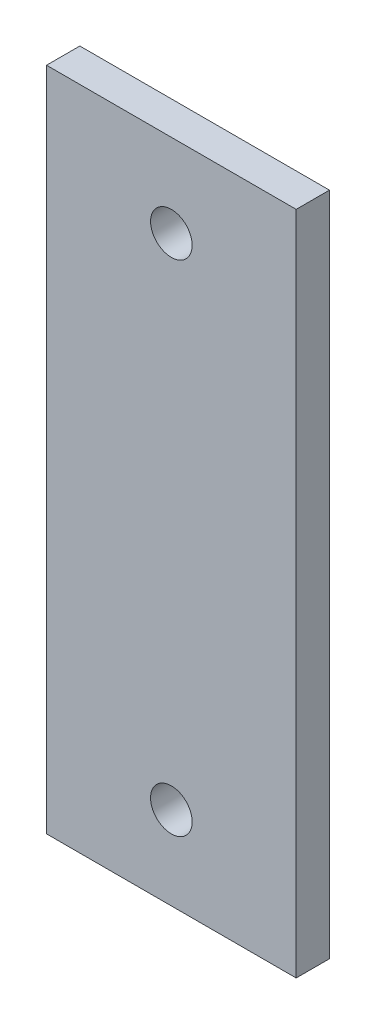
SolidWorks part; units mm, degrees
material "Balsa"
ref_plane "Plan de face" through (0, 0, 0) normal (0, 0, 1) x (1, 0, 0)
ref_plane "Plan de dessus" through (0, 0, 0) normal (0, 1, 0) x (1, 0, 0)
ref_plane "Plan de droite" through (0, 0, 0) normal (1, 0, 0) x (0, 0, -1)
sketch "Esquisse1" plane through (0, 0, 0) normal (0, 0, 1) x (1, 0, 0)
  line L0 (-10.4451, 0) -> (0, 0) construction
  line L5 (-15, 40) -> (15, 40)
  line L6 (-15, 40) -> (-15, -40)
  line L7 (-15, -40) -> (15, -40)
  line L8 (15, 40) -> (15, -40)
  line L9 (-15, 40) -> (15, -40) construction
  line L10 (-15, -40) -> (15, 40) construction
  circle A8 centre (0, 30) radius 2.5
  circle A10 centre (0, -30) radius 2.5
  point P0 (0, 0)
  dimension "D3" = 10
  dimension "D4" = 5
  dimension "D1" = 80
  dimension "D2" = 30
extrude "Boss.-Extru.1" add sketch "Esquisse1" along normal blind 4
